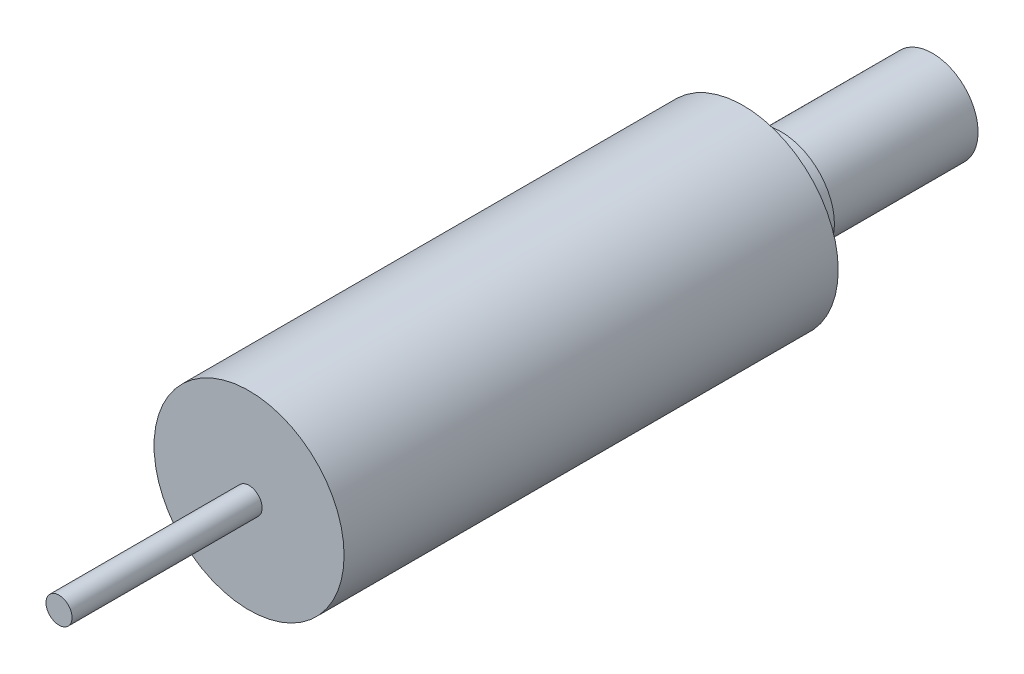
SolidWorks part; units mm, degrees
ref_plane "Front Plane" through (0, 0, 0) normal (0, 0, 1) x (1, 0, 0)
ref_plane "Top Plane" through (0, 0, 0) normal (0, 1, 0) x (1, 0, 0)
ref_plane "Right Plane" through (0, 0, 0) normal (1, 0, 0) x (0, 0, -1)
sketch "Sketch1" plane through (0, 0, 0) normal (0, 0, 1) x (1, 0, 0)
  circle A0 centre (0, 0) radius 6
  dimension "D1" = 12
extrude "Bearing Journal-12mm" add sketch "Sketch1" along normal blind 19.9 contours A0
sketch "Sketch2" plane through (0, 0, 19.9) normal (0, 0, 1) x (1, 0, 0)
  circle A0 centre (0, 0) radius 7
  dimension "D1" = 14
extrude "Boss-Extrude2" add sketch "Sketch2" along normal blind 5
sketch "Sketch3" plane through (0, 0, 24.9) normal (0, 0, 1) x (1, 0, 0)
  circle A0 centre (0, 0) radius 12.5
  dimension "D1" = 25
extrude "Body-M25" add sketch "Sketch3" along normal blind 65
sketch "Sketch4" plane through (0, 0, 89.9) normal (0, 0, 1) x (1, 0, 0)
  circle A0 centre (0, 0) radius 1.7149
extrude "Cable" add sketch "Sketch4" along normal blind 25
sketch "Sketch5" plane through (0, 0, 0) normal (0, 0, -1) x (-1, 0, 0)
  circle A0 centre (0, 0) radius 3
  dimension "D1" = 6
extrude "M6" cut sketch "Sketch5" against normal blind 10
